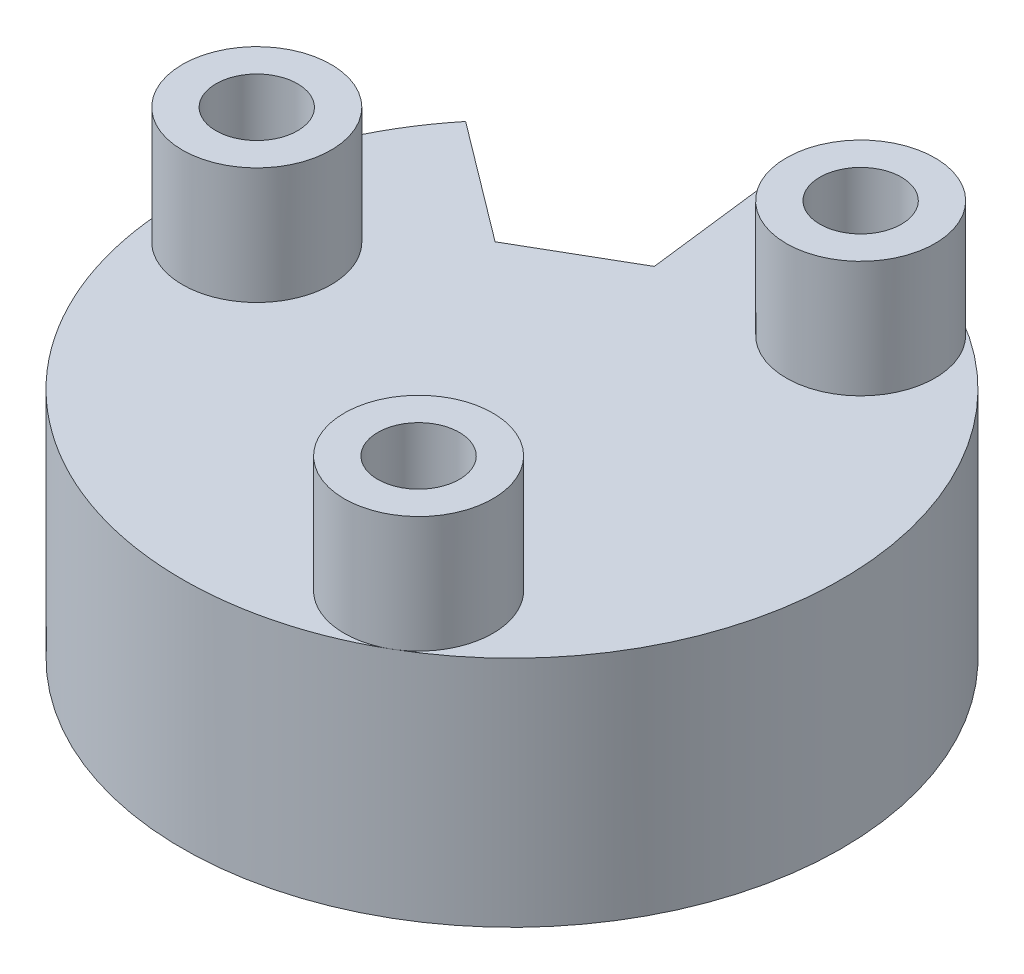
SolidWorks part; units mm, degrees
material "AISI 1020"
ref_plane "Plan de face" through (0, 0, 0) normal (0, 0, 1) x (1, 0, 0)
ref_plane "Plan de dessus" through (0, 0, 0) normal (0, 1, 0) x (1, 0, 0)
ref_plane "Plan de droite" through (0, 0, 0) normal (1, 0, 0) x (0, 0, -1)
sketch "Sketch3" plane through (0, 0, 0) normal (0, 1, 0) x (1, 0, 0)
  line L0 (-55, 0) -> (55, 0) construction
  line L1 (-21.8841, 17.9043) -> (-11.679, 10.2287)
  line L2 (-4.5635, 27.9043) -> (-3.0188, 15.2287)
  line L3 (0, -55) -> (0, 55) construction
  line L4 (-11.679, 10.2287) -> (-3.0188, 15.2287)
  line L5 (0, 0) -> (-23.4544, 40.6243) construction
  arc A0 (-21.8841, 17.9043) -> (-4.5635, 27.9043) centre (0, 0) ccw
  circle A1 centre (0, 0) radius 21.9 construction
  circle A2 centre (-21.9, 0) radius 6.375 construction
  circle A3 centre (10.95, 18.966) radius 6.375 construction
  circle A4 centre (10.95, -18.966) radius 6.375 construction
  circle A5 centre (0, 0) radius 15.525 construction
  point P1 (-23.4544, 40.6243)
  point P15 (0, 0)
  dimension "D1" = 3
  dimension "D2" = 10
  dimension "D3" = 20
extrude "Boss-Extrude1" add sketch "Sketch3" along normal blind 20
sketch "Sketch4" plane through (0, 20, 0) normal (0, 1, 0) x (1, 0, 0)
  line L0 (-55, 0) -> (55, 0) construction
  circle A0 centre (0, 0) radius 21.9 construction
  circle A1 centre (-21.9, 0) radius 6.375
  circle A2 centre (10.95, 18.966) radius 6.375
  circle A3 centre (10.95, -18.966) radius 6.375
  point P13 (0, 0)
  dimension "D1" = 3
extrude "Boss-Extrude2" add sketch "Sketch4" along normal blind 10
sketch "Sketch5" plane through (0, 0, 0) normal (0, -1, 0) x (1, 0, 0)
  line L0 (0.9041, -4.1015) -> (-4.0041, -1.2678)
  line L1 (5.6579, 1.5832) -> (5.7088, 1.5538) construction
  line L2 (-3.0188, -15.2287) -> (-11.679, -10.2287) construction
  arc A0 (0.9041, -4.1015) -> (-4.0041, -1.2678) centre (0, 0) ccw
  dimension "D1" = 4.2
  dimension "D2" = 7.3
extrude "Cut-Extrude1" cut sketch "Sketch5" against normal blind 12
hole_wizard "Dégagement M1.61" positions "Esquisse8" profile "Esquisse9" hole size "M1.6" standard "Ansi Metric" end condition through all
sketch "Esquisse8" plane through (0, 30, 0) normal (0, 1, 0) x (1, 0, 0)
  point P0 (10.95, 18.966)
  point P3 (10.95, -18.966)
  point P6 (-21.9, 0)
sketch "Esquisse9" plane through (10.95, 30, -18.966) normal (1, 0, 0) x (0, 0, 1)
  line L0 (0, 0) -> (0, 30)
  line L1 (0, 30) -> (3.5, 30)
  line L2 (3.5, 30) -> (3.5, 0)
  line L5 (3.5, 0) -> (0, 0)
  line L11 (0, -6.35) -> (0, 107.95) construction
  dimension "Diamètre du perçage jusqu'au prochain" = 7
  dimension "Profondeur du perçage jusqu'au prochain" = 30
hole_wizard "Dégagement M21" positions "Esquisse10" profile "Esquisse11" hole size "M2" standard "Ansi Metric"
sketch "Esquisse10" plane through (-7.3489, 0, -12.7287) normal (-0.5, 0, -0.866) x (-0.866, 0, 0.5)
  line L0 (-5, 0) -> (5, 0) construction
  point P0 (0, 5)
  dimension "D1" = 5
sketch "Esquisse11" plane through (-7.3489, 5, -12.7287) normal (0, 1, 0) x (-0.866, 0, 0.5)
  line L0 (0, 0) -> (0, 11.5978)
  line L1 (0, 11.5978) -> (1.65, 11.5978)
  line L2 (1.65, 11.5978) -> (1.65, 0)
  line L5 (1.65, 0) -> (0, 0)
  line L11 (0, -6.35) -> (0, 107.95) construction
  dimension "Diamètre du perçage jusqu'au prochain" = 3.3
  dimension "Profondeur du perçage jusqu'au prochain" = 11.5978
